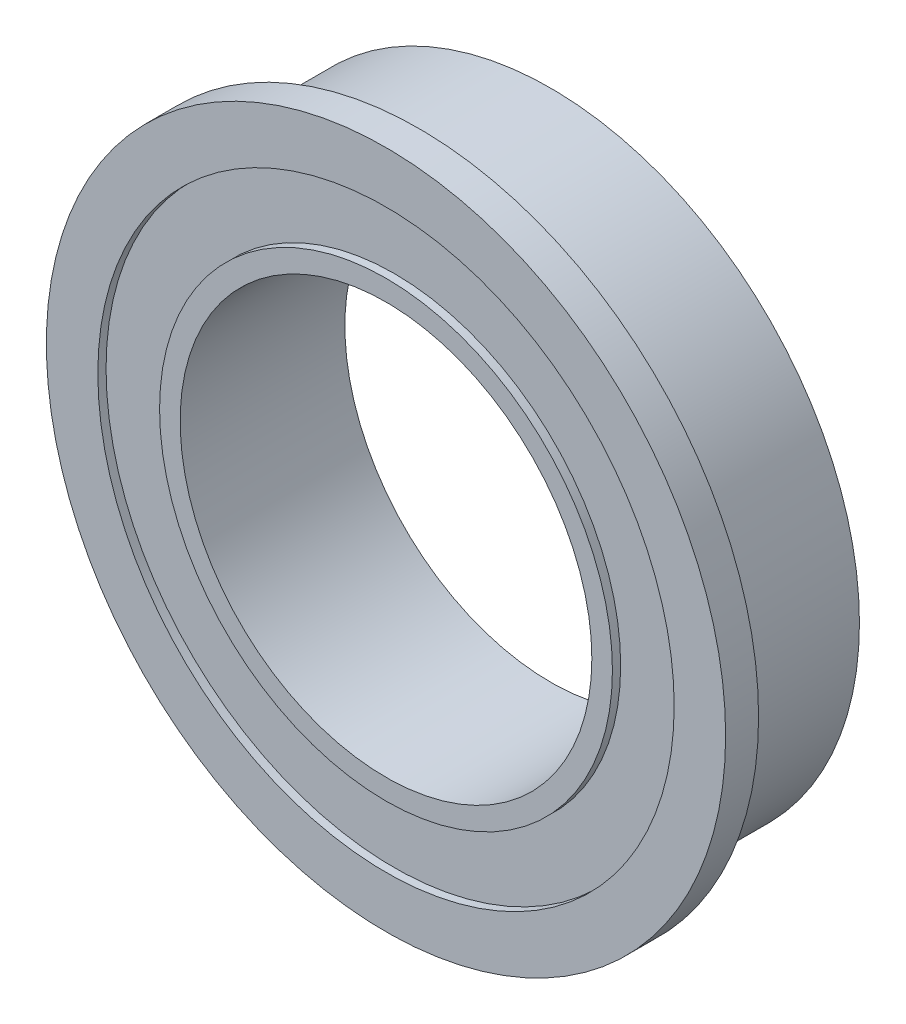
SolidWorks part; units mm, degrees
ref_plane "前视基准面" through (0, 0, 0) normal (0, 0, 1) x (1, 0, 0)
ref_plane "上视基准面" through (0, 0, 0) normal (0, 1, 0) x (1, 0, 0)
ref_plane "右视基准面" through (0, 0, 0) normal (1, 0, 0) x (0, 0, -1)
sketch "草图1" plane through (0, 0, 0) normal (0, 0, 1) x (1, 0, 0)
  circle A0 centre (0, 0) radius 7.5
  circle A1 centre (0, 0) radius 8.25
  dimension "D1" = 15
  dimension "D2" = 16.5
extrude "凸台-拉伸1" add sketch "草图1" along normal blind 0.8
sketch "草图2" plane through (0, 0, 0.8) normal (0, 0, 1) x (1, 0, 0)
  circle A0 centre (0, 0) radius 7.5
  circle A1 centre (0, 0) radius 5
  circle A3 centre (0, 0) radius 7.5 construction
  dimension "D2" = 10
extrude "凸台-拉伸2" add sketch "草图2" against normal blind 4
sketch "草图3" plane through (0, 0, -3.2) normal (0, 0, -1) x (-1, 0, 0)
  circle A0 centre (0, 0) radius 5.5
  circle A1 centre (0, 0) radius 7
  circle A2 centre (0, 0) radius 7.5 construction
  circle A3 centre (0, 0) radius 5 construction
  dimension "D1" = 0.5
  dimension "D2" = 0.5
extrude "切除-拉伸1" cut sketch "草图3" against normal blind 0.2
ref_plane "基准面1" through (0, 0, -1.2) normal (0, 0, -1) x (-1, 0, 0)
mirror "镜向1" about plane through (0, 0, -1.2) normal (0, 0, -1) of "切除-拉伸1"
